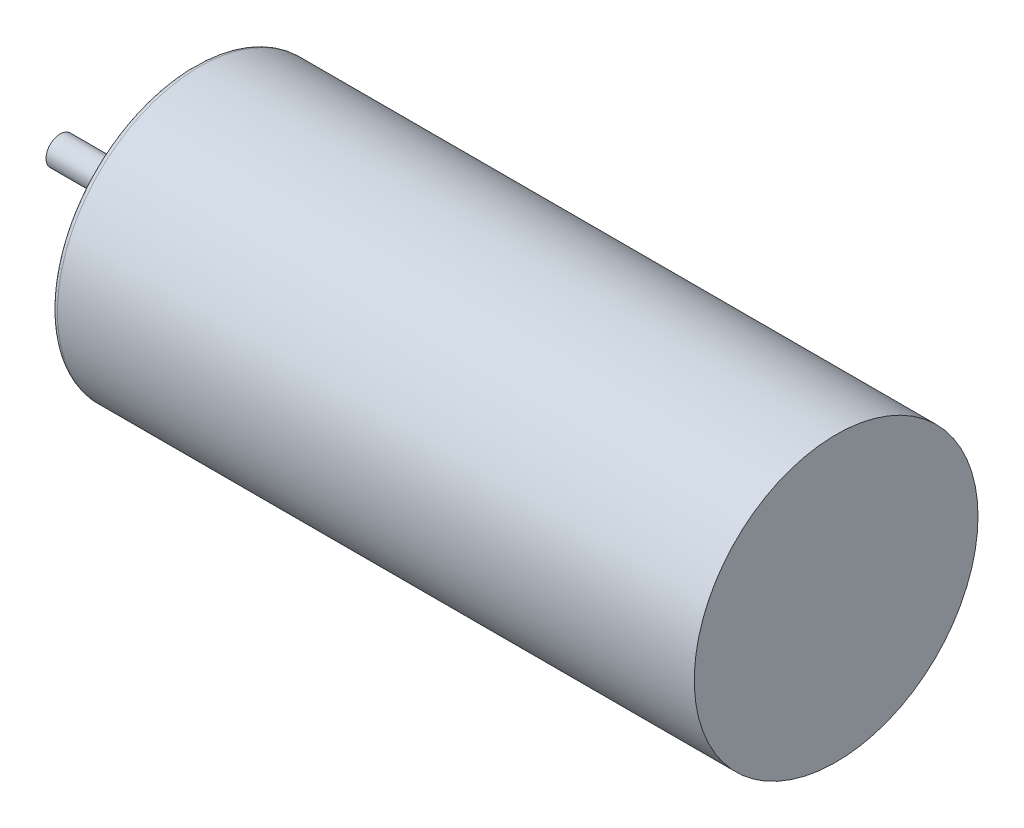
SolidWorks part; units mm, degrees
ref_plane "Plano frontal" through (0, 0, 0) normal (0, 0, 1) x (1, 0, 0)
ref_plane "Plano superior" through (0, 0, 0) normal (0, 1, 0) x (1, 0, 0)
ref_plane "Plano direito" through (0, 0, 0) normal (1, 0, 0) x (0, 0, -1)
sketch "Esboço2" plane through (0, 0, 0) normal (1, 0, 0) x (0, 0, -1)
  circle A0 centre (0, 0) radius 5
  dimension "D1" = 10
extrude "Ressalto-extrusão1" add sketch "Esboço2" against normal blind 22.65
sketch "Esboço3" plane through (-22.65, 0, 0) normal (-1, 0, 0) x (0, 0, 1)
  circle A0 centre (0, 0) radius 0.5
  dimension "D1" = 1
extrude "Ressalto-extrusão2" add sketch "Esboço3" along normal blind 4.7
sketch "Esboço4" plane through (-22.65, 0, 0) normal (-1, 0, 0) x (0, 0, 1)
  circle A0 centre (0, 0) radius 1
  dimension "D1" = 2
extrude "Ressalto-extrusão3" add sketch "Esboço4" along normal blind 0.5
fillet "Filete1" radius 0.2 1 edges at (-22.65, 0, -5)
